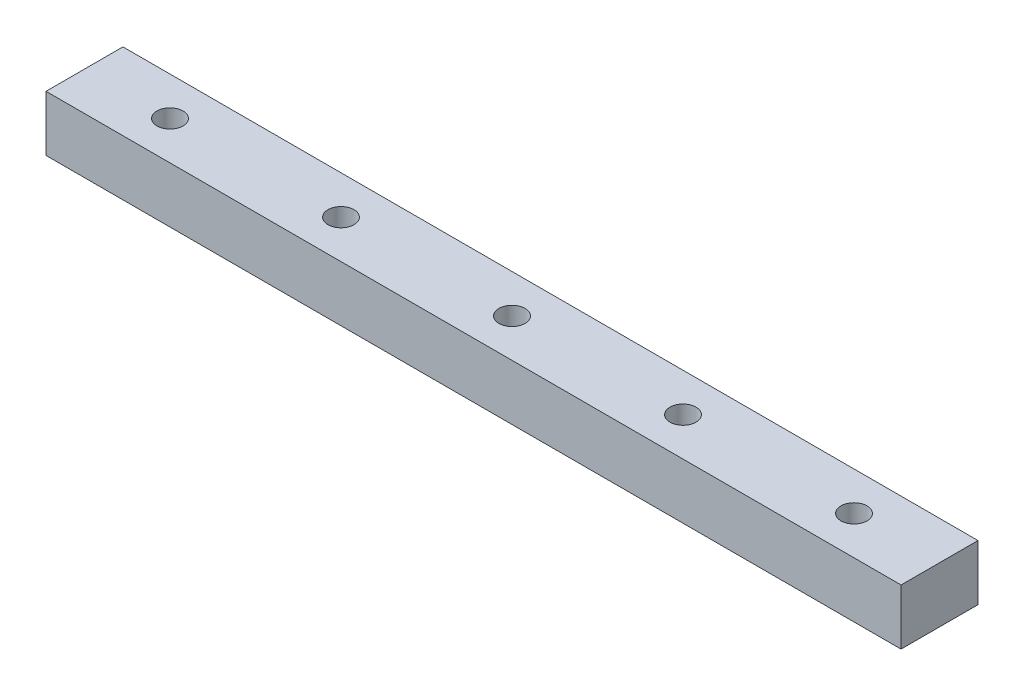
SolidWorks part; units mm, degrees
ref_plane "前视基准面" through (0, 0, 0) normal (0, 0, 1) x (1, 0, 0)
ref_plane "上视基准面" through (0, 0, 0) normal (0, 1, 0) x (1, 0, 0)
ref_plane "右视基准面" through (0, 0, 0) normal (1, 0, 0) x (0, 0, -1)
other "Configuration Table"
sketch "草图1" plane through (0, 0, 0) normal (1, 0, 0) x (0, 0, -1)
  line L1 (0, 0) -> (9, 0)
  line L2 (0, 0) -> (0, 6.5)
  line L3 (0, 6.5) -> (9, 6.5)
  line L4 (9, 0) -> (9, 6.5)
  dimension "D1" = 6.5
  dimension "D2" = 9
extrude "凸台-拉伸1" add sketch "草图1" along normal blind 100
sketch "草图2" plane through (0, 6.5, 0) normal (0, 1, 0) x (1, 0, 0)
  line L0 (0, 4.5) -> (10, 4.5) construction
  line L1 (0, 9) -> (0, 0) construction
  circle A0 centre (10, 4.5) radius 1.525
  circle A1 centre (30, 4.5) radius 1.525
  circle A2 centre (50, 4.5) radius 1.525
  circle A3 centre (70, 4.5) radius 1.525
  circle A4 centre (90, 4.5) radius 1.525
  dimension "D1" = 3.05
  dimension "D4" = 20
  dimension "D2" = 10
  dimension "D3" = 5
extrude "切除-拉伸1" cut sketch "草图2" against normal through all
